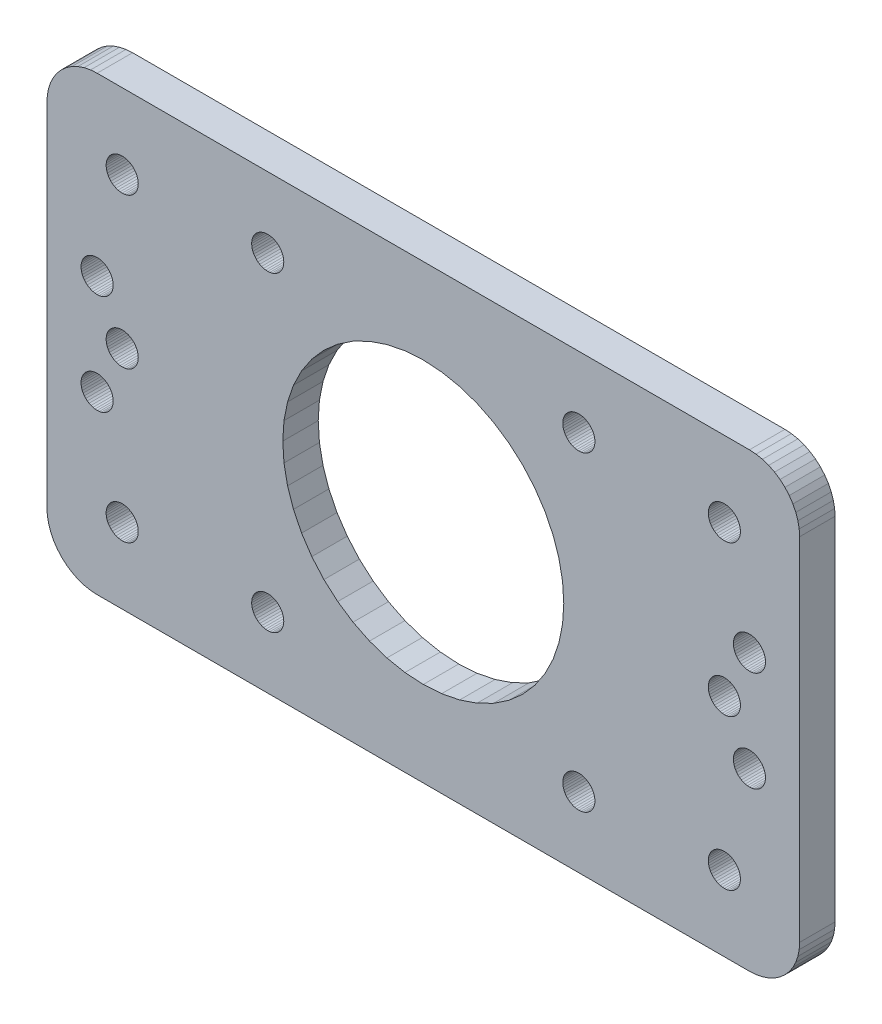
SolidWorks part; units mm, degrees
ref_plane "Front Plane" through (0, 0, 0) normal (0, 0, 1) x (1, 0, 0)
ref_plane "Top Plane" through (0, 0, 0) normal (0, 1, 0) x (1, 0, 0)
ref_plane "Right Plane" through (0, 0, 0) normal (1, 0, 0) x (0, 0, -1)
ref_plane "Plane4" through (0, 0, 3.532) normal (0, 0, 1) x (1, 0, 0)
sketch "Sketch1" plane through (0, 0, 3.532) normal (0, 0, 1) x (1, 0, 0)
  line L0 (5.9545, 22.0859) -> (5.9137, 22.2912)
  line L1 (5.9137, 22.2912) -> (5.9, 22.5)
  line L2 (5.9, 22.5) -> (5.9137, 22.7088)
  line L3 (5.9137, 22.7088) -> (5.9545, 22.9141)
  line L4 (5.9545, 22.9141) -> (6.0218, 23.1123)
  line L5 (6.0218, 23.1123) -> (6.1144, 23.3)
  line L6 (6.1144, 23.3) -> (6.2306, 23.474)
  line L7 (6.2306, 23.474) -> (6.3686, 23.6314)
  line L8 (6.3686, 23.6314) -> (6.526, 23.7694)
  line L9 (6.526, 23.7694) -> (6.7, 23.8856)
  line L10 (6.7, 23.8856) -> (6.8877, 23.9782)
  line L11 (6.8877, 23.9782) -> (7.0859, 24.0455)
  line L12 (7.0859, 24.0455) -> (7.2912, 24.0863)
  line L13 (7.2912, 24.0863) -> (7.5, 24.1)
  line L14 (7.5, 24.1) -> (7.7088, 24.0863)
  line L15 (7.7088, 24.0863) -> (7.9141, 24.0455)
  line L16 (7.9141, 24.0455) -> (8.1123, 23.9782)
  line L17 (8.1123, 23.9782) -> (8.3, 23.8856)
  line L18 (8.3, 23.8856) -> (8.474, 23.7694)
  line L19 (8.474, 23.7694) -> (8.6314, 23.6314)
  line L20 (8.6314, 23.6314) -> (8.7694, 23.474)
  line L21 (8.7694, 23.474) -> (8.8856, 23.3)
  line L22 (8.8856, 23.3) -> (8.9782, 23.1123)
  line L23 (8.9782, 23.1123) -> (9.0455, 22.9141)
  line L24 (9.0455, 22.9141) -> (9.0863, 22.7088)
  line L25 (9.0863, 22.7088) -> (9.1, 22.5)
  line L26 (9.1, 22.5) -> (9.0863, 22.2912)
  line L27 (9.0863, 22.2912) -> (9.0455, 22.0859)
  line L28 (9.0455, 22.0859) -> (8.9782, 21.8877)
  line L29 (8.9782, 21.8877) -> (8.8856, 21.7)
  line L30 (8.8856, 21.7) -> (8.7694, 21.526)
  line L31 (8.7694, 21.526) -> (8.6314, 21.3686)
  line L32 (8.6314, 21.3686) -> (8.474, 21.2306)
  line L33 (8.474, 21.2306) -> (8.3, 21.1144)
  line L34 (8.3, 21.1144) -> (8.1123, 21.0218)
  line L35 (8.1123, 21.0218) -> (7.9141, 20.9545)
  line L36 (7.9141, 20.9545) -> (7.7088, 20.9137)
  line L37 (7.7088, 20.9137) -> (7.5, 20.9)
  line L38 (7.5, 20.9) -> (7.2912, 20.9137)
  line L39 (7.2912, 20.9137) -> (7.0859, 20.9545)
  line L40 (7.0859, 20.9545) -> (6.8877, 21.0218)
  line L41 (6.8877, 21.0218) -> (6.7, 21.1144)
  line L42 (6.7, 21.1144) -> (6.526, 21.2306)
  line L43 (6.526, 21.2306) -> (6.3686, 21.3686)
  line L44 (6.3686, 21.3686) -> (6.2306, 21.526)
  line L45 (6.2306, 21.526) -> (6.1144, 21.7)
  line L46 (6.1144, 21.7) -> (6.0218, 21.8877)
  line L47 (6.0218, 21.8877) -> (5.9545, 22.0859)
  line L48 (5.6123, 18.9782) -> (5.8, 18.8856)
  line L49 (5.8, 18.8856) -> (5.974, 18.7694)
  line L50 (5.974, 18.7694) -> (6.1314, 18.6314)
  line L51 (6.1314, 18.6314) -> (6.2694, 18.474)
  line L52 (6.2694, 18.474) -> (6.3856, 18.3)
  line L53 (6.3856, 18.3) -> (6.4782, 18.1123)
  line L54 (6.4782, 18.1123) -> (6.5455, 17.9141)
  line L55 (6.5455, 17.9141) -> (6.5863, 17.7088)
  line L56 (6.5863, 17.7088) -> (6.6, 17.5)
  line L57 (6.6, 17.5) -> (6.5863, 17.2912)
  line L58 (6.5863, 17.2912) -> (6.5455, 17.0859)
  line L59 (6.5455, 17.0859) -> (6.4782, 16.8877)
  line L60 (6.4782, 16.8877) -> (6.3856, 16.7)
  line L61 (6.3856, 16.7) -> (6.2694, 16.526)
  line L62 (6.2694, 16.526) -> (6.1314, 16.3686)
  line L63 (6.1314, 16.3686) -> (5.974, 16.2306)
  line L64 (5.974, 16.2306) -> (5.8, 16.1144)
  line L65 (5.8, 16.1144) -> (5.6123, 16.0218)
  line L66 (5.6123, 16.0218) -> (5.4141, 15.9545)
  line L67 (5.4141, 15.9545) -> (5.2088, 15.9137)
  line L68 (5.2088, 15.9137) -> (5, 15.9)
  line L69 (5, 15.9) -> (4.7912, 15.9137)
  line L70 (4.7912, 15.9137) -> (4.5859, 15.9545)
  line L71 (4.5859, 15.9545) -> (4.3877, 16.0218)
  line L72 (4.3877, 16.0218) -> (4.2, 16.1144)
  line L73 (4.2, 16.1144) -> (4.026, 16.2306)
  line L74 (4.026, 16.2306) -> (3.8686, 16.3686)
  line L75 (3.8686, 16.3686) -> (3.7306, 16.526)
  line L76 (3.7306, 16.526) -> (3.6144, 16.7)
  line L77 (3.6144, 16.7) -> (3.5218, 16.8877)
  line L78 (3.5218, 16.8877) -> (3.4545, 17.0859)
  line L79 (3.4545, 17.0859) -> (3.4137, 17.2912)
  line L80 (3.4137, 17.2912) -> (3.4, 17.5)
  line L81 (3.4, 17.5) -> (3.4137, 17.7088)
  line L82 (3.4137, 17.7088) -> (3.4545, 17.9141)
  line L83 (3.4545, 17.9141) -> (3.5218, 18.1123)
  line L84 (3.5218, 18.1123) -> (3.6144, 18.3)
  line L85 (3.6144, 18.3) -> (3.7306, 18.474)
  line L86 (3.7306, 18.474) -> (3.8686, 18.6314)
  line L87 (3.8686, 18.6314) -> (4.026, 18.7694)
  line L88 (4.026, 18.7694) -> (4.2, 18.8856)
  line L89 (4.2, 18.8856) -> (4.3877, 18.9782)
  line L90 (4.3877, 18.9782) -> (4.5859, 19.0455)
  line L91 (4.5859, 19.0455) -> (4.7912, 19.0863)
  line L92 (4.7912, 19.0863) -> (5, 19.1)
  line L93 (5, 19.1) -> (5.2088, 19.0863)
  line L94 (5.2088, 19.0863) -> (5.4141, 19.0455)
  line L95 (5.4141, 19.0455) -> (5.6123, 18.9782)
  line L96 (69.3877, 18.9782) -> (69.5859, 19.0455)
  line L97 (69.5859, 19.0455) -> (69.7912, 19.0863)
  line L98 (69.7912, 19.0863) -> (70, 19.1)
  line L99 (70, 19.1) -> (70.2088, 19.0863)
  line L100 (70.2088, 19.0863) -> (70.4141, 19.0455)
  line L101 (70.4141, 19.0455) -> (70.6123, 18.9782)
  line L102 (70.6123, 18.9782) -> (70.8, 18.8856)
  line L103 (70.8, 18.8856) -> (70.974, 18.7694)
  line L104 (70.974, 18.7694) -> (71.1314, 18.6314)
  line L105 (71.1314, 18.6314) -> (71.2694, 18.474)
  line L106 (71.2694, 18.474) -> (71.3856, 18.3)
  line L107 (71.3856, 18.3) -> (71.4782, 18.1123)
  line L108 (71.4782, 18.1123) -> (71.5455, 17.9141)
  line L109 (71.5455, 17.9141) -> (71.5863, 17.7088)
  line L110 (71.5863, 17.7088) -> (71.6, 17.5)
  line L111 (71.6, 17.5) -> (71.5863, 17.2912)
  line L112 (71.5863, 17.2912) -> (71.5455, 17.0859)
  line L113 (71.5455, 17.0859) -> (71.4782, 16.8877)
  line L114 (71.4782, 16.8877) -> (71.3856, 16.7)
  line L115 (71.3856, 16.7) -> (71.2694, 16.526)
  line L116 (71.2694, 16.526) -> (71.1314, 16.3686)
  line L117 (71.1314, 16.3686) -> (70.974, 16.2306)
  line L118 (70.974, 16.2306) -> (70.8, 16.1144)
  line L119 (70.8, 16.1144) -> (70.6123, 16.0218)
  line L120 (70.6123, 16.0218) -> (70.4141, 15.9545)
  line L121 (70.4141, 15.9545) -> (70.2088, 15.9137)
  line L122 (70.2088, 15.9137) -> (70, 15.9)
  line L123 (70, 15.9) -> (69.7912, 15.9137)
  line L124 (69.7912, 15.9137) -> (69.5859, 15.9545)
  line L125 (69.5859, 15.9545) -> (69.3877, 16.0218)
  line L126 (69.3877, 16.0218) -> (69.2, 16.1144)
  line L127 (69.2, 16.1144) -> (69.026, 16.2306)
  line L128 (69.026, 16.2306) -> (68.8686, 16.3686)
  line L129 (68.8686, 16.3686) -> (68.7306, 16.526)
  line L130 (68.7306, 16.526) -> (68.6144, 16.7)
  line L131 (68.6144, 16.7) -> (68.5218, 16.8877)
  line L132 (68.5218, 16.8877) -> (68.4545, 17.0859)
  line L133 (68.4545, 17.0859) -> (68.4137, 17.2912)
  line L134 (68.4137, 17.2912) -> (68.4, 17.5)
  line L135 (68.4, 17.5) -> (68.4137, 17.7088)
  line L136 (68.4137, 17.7088) -> (68.4545, 17.9141)
  line L137 (68.4545, 17.9141) -> (68.5218, 18.1123)
  line L138 (68.5218, 18.1123) -> (68.6144, 18.3)
  line L139 (68.6144, 18.3) -> (68.7306, 18.474)
  line L140 (68.7306, 18.474) -> (68.8686, 18.6314)
  line L141 (68.8686, 18.6314) -> (69.026, 18.7694)
  line L142 (69.026, 18.7694) -> (69.2, 18.8856)
  line L143 (69.2, 18.8856) -> (69.3877, 18.9782)
  line L144 (69.0863, 22.7088) -> (69.1, 22.5)
  line L145 (69.1, 22.5) -> (69.0863, 22.2912)
  line L146 (69.0863, 22.2912) -> (69.0455, 22.0859)
  line L147 (69.0455, 22.0859) -> (68.9782, 21.8877)
  line L148 (68.9782, 21.8877) -> (68.8856, 21.7)
  line L149 (68.8856, 21.7) -> (68.7694, 21.526)
  line L150 (68.7694, 21.526) -> (68.6314, 21.3686)
  line L151 (68.6314, 21.3686) -> (68.474, 21.2306)
  line L152 (68.474, 21.2306) -> (68.3, 21.1144)
  line L153 (68.3, 21.1144) -> (68.1123, 21.0218)
  line L154 (68.1123, 21.0218) -> (67.9141, 20.9545)
  line L155 (67.9141, 20.9545) -> (67.7088, 20.9137)
  line L156 (67.7088, 20.9137) -> (67.5, 20.9)
  line L157 (67.5, 20.9) -> (67.2912, 20.9137)
  line L158 (67.2912, 20.9137) -> (67.0859, 20.9545)
  line L159 (67.0859, 20.9545) -> (66.8877, 21.0218)
  line L160 (66.8877, 21.0218) -> (66.7, 21.1144)
  line L161 (66.7, 21.1144) -> (66.526, 21.2306)
  line L162 (66.526, 21.2306) -> (66.3686, 21.3686)
  line L163 (66.3686, 21.3686) -> (66.2306, 21.526)
  line L164 (66.2306, 21.526) -> (66.1144, 21.7)
  line L165 (66.1144, 21.7) -> (66.0218, 21.8877)
  line L166 (66.0218, 21.8877) -> (65.9545, 22.0859)
  line L167 (65.9545, 22.0859) -> (65.9137, 22.2912)
  line L168 (65.9137, 22.2912) -> (65.9, 22.5)
  line L169 (65.9, 22.5) -> (65.9137, 22.7088)
  line L170 (65.9137, 22.7088) -> (65.9545, 22.9141)
  line L171 (65.9545, 22.9141) -> (66.0218, 23.1123)
  line L172 (66.0218, 23.1123) -> (66.1144, 23.3)
  line L173 (66.1144, 23.3) -> (66.2306, 23.474)
  line L174 (66.2306, 23.474) -> (66.3686, 23.6314)
  line L175 (66.3686, 23.6314) -> (66.526, 23.7694)
  line L176 (66.526, 23.7694) -> (66.7, 23.8856)
  line L177 (66.7, 23.8856) -> (66.8877, 23.9782)
  line L178 (66.8877, 23.9782) -> (67.0859, 24.0455)
  line L179 (67.0859, 24.0455) -> (67.2912, 24.0863)
  line L180 (67.2912, 24.0863) -> (67.5, 24.1)
  line L181 (67.5, 24.1) -> (67.7088, 24.0863)
  line L182 (67.7088, 24.0863) -> (67.9141, 24.0455)
  line L183 (67.9141, 24.0455) -> (68.1123, 23.9782)
  line L184 (68.1123, 23.9782) -> (68.3, 23.8856)
  line L185 (68.3, 23.8856) -> (68.474, 23.7694)
  line L186 (68.474, 23.7694) -> (68.6314, 23.6314)
  line L187 (68.6314, 23.6314) -> (68.7694, 23.474)
  line L188 (68.7694, 23.474) -> (68.8856, 23.3)
  line L189 (68.8856, 23.3) -> (68.9782, 23.1123)
  line L190 (68.9782, 23.1123) -> (69.0455, 22.9141)
  line L191 (69.0455, 22.9141) -> (69.0863, 22.7088)
  line L192 (6.3686, 8.6314) -> (6.526, 8.7694)
  line L193 (6.526, 8.7694) -> (6.7, 8.8856)
  line L194 (6.7, 8.8856) -> (6.8877, 8.9782)
  line L195 (6.8877, 8.9782) -> (7.0859, 9.0455)
  line L196 (7.0859, 9.0455) -> (7.2912, 9.0863)
  line L197 (7.2912, 9.0863) -> (7.5, 9.1)
  line L198 (7.5, 9.1) -> (7.7088, 9.0863)
  line L199 (7.7088, 9.0863) -> (7.9141, 9.0455)
  line L200 (7.9141, 9.0455) -> (8.1123, 8.9782)
  line L201 (8.1123, 8.9782) -> (8.3, 8.8856)
  line L202 (8.3, 8.8856) -> (8.474, 8.7694)
  line L203 (8.474, 8.7694) -> (8.6314, 8.6314)
  line L204 (8.6314, 8.6314) -> (8.7694, 8.474)
  line L205 (8.7694, 8.474) -> (8.8856, 8.3)
  line L206 (8.8856, 8.3) -> (8.9782, 8.1123)
  line L207 (8.9782, 8.1123) -> (9.0455, 7.9141)
  line L208 (9.0455, 7.9141) -> (9.0863, 7.7088)
  line L209 (9.0863, 7.7088) -> (9.1, 7.5)
  line L210 (9.1, 7.5) -> (9.0863, 7.2912)
  line L211 (9.0863, 7.2912) -> (9.0455, 7.0859)
  line L212 (9.0455, 7.0859) -> (8.9782, 6.8877)
  line L213 (8.9782, 6.8877) -> (8.8856, 6.7)
  line L214 (8.8856, 6.7) -> (8.7694, 6.526)
  line L215 (8.7694, 6.526) -> (8.6314, 6.3686)
  line L216 (8.6314, 6.3686) -> (8.474, 6.2306)
  line L217 (8.474, 6.2306) -> (8.3, 6.1144)
  line L218 (8.3, 6.1144) -> (8.1123, 6.0218)
  line L219 (8.1123, 6.0218) -> (7.9141, 5.9545)
  line L220 (7.9141, 5.9545) -> (7.7088, 5.9137)
  line L221 (7.7088, 5.9137) -> (7.5, 5.9)
  line L222 (7.5, 5.9) -> (7.2912, 5.9137)
  line L223 (7.2912, 5.9137) -> (7.0859, 5.9545)
  line L224 (7.0859, 5.9545) -> (6.8877, 6.0218)
  line L225 (6.8877, 6.0218) -> (6.7, 6.1144)
  line L226 (6.7, 6.1144) -> (6.526, 6.2306)
  line L227 (6.526, 6.2306) -> (6.3686, 6.3686)
  line L228 (6.3686, 6.3686) -> (6.2306, 6.526)
  line L229 (6.2306, 6.526) -> (6.1144, 6.7)
  line L230 (6.1144, 6.7) -> (6.0218, 6.8877)
  line L231 (6.0218, 6.8877) -> (5.9545, 7.0859)
  line L232 (5.9545, 7.0859) -> (5.9137, 7.2912)
  line L233 (5.9137, 7.2912) -> (5.9, 7.5)
  line L234 (5.9, 7.5) -> (5.9137, 7.7088)
  line L235 (5.9137, 7.7088) -> (5.9545, 7.9141)
  line L236 (5.9545, 7.9141) -> (6.0218, 8.1123)
  line L237 (6.0218, 8.1123) -> (6.1144, 8.3)
  line L238 (6.1144, 8.3) -> (6.2306, 8.474)
  line L239 (6.2306, 8.474) -> (6.3686, 8.6314)
  line L240 (68.3, 8.8856) -> (68.474, 8.7694)
  line L241 (68.474, 8.7694) -> (68.6314, 8.6314)
  line L242 (68.6314, 8.6314) -> (68.7694, 8.474)
  line L243 (68.7694, 8.474) -> (68.8856, 8.3)
  line L244 (68.8856, 8.3) -> (68.9782, 8.1123)
  line L245 (68.9782, 8.1123) -> (69.0455, 7.9141)
  line L246 (69.0455, 7.9141) -> (69.0863, 7.7088)
  line L247 (69.0863, 7.7088) -> (69.1, 7.5)
  line L248 (69.1, 7.5) -> (69.0863, 7.2912)
  line L249 (69.0863, 7.2912) -> (69.0455, 7.0859)
  line L250 (69.0455, 7.0859) -> (68.9782, 6.8877)
  line L251 (68.9782, 6.8877) -> (68.8856, 6.7)
  line L252 (68.8856, 6.7) -> (68.7694, 6.526)
  line L253 (68.7694, 6.526) -> (68.6314, 6.3686)
  line L254 (68.6314, 6.3686) -> (68.474, 6.2306)
  line L255 (68.474, 6.2306) -> (68.3, 6.1144)
  line L256 (68.3, 6.1144) -> (68.1123, 6.0218)
  line L257 (68.1123, 6.0218) -> (67.9141, 5.9545)
  line L258 (67.9141, 5.9545) -> (67.7088, 5.9137)
  line L259 (67.7088, 5.9137) -> (67.5, 5.9)
  line L260 (67.5, 5.9) -> (67.2912, 5.9137)
  line L261 (67.2912, 5.9137) -> (67.0859, 5.9545)
  line L262 (67.0859, 5.9545) -> (66.8877, 6.0218)
  line L263 (66.8877, 6.0218) -> (66.7, 6.1144)
  line L264 (66.7, 6.1144) -> (66.526, 6.2306)
  line L265 (66.526, 6.2306) -> (66.3686, 6.3686)
  line L266 (66.3686, 6.3686) -> (66.2306, 6.526)
  line L267 (66.2306, 6.526) -> (66.1144, 6.7)
  line L268 (66.1144, 6.7) -> (66.0218, 6.8877)
  line L269 (66.0218, 6.8877) -> (65.9545, 7.0859)
  line L270 (65.9545, 7.0859) -> (65.9137, 7.2912)
  line L271 (65.9137, 7.2912) -> (65.9, 7.5)
  line L272 (65.9, 7.5) -> (65.9137, 7.7088)
  line L273 (65.9137, 7.7088) -> (65.9545, 7.9141)
  line L274 (65.9545, 7.9141) -> (66.0218, 8.1123)
  line L275 (66.0218, 8.1123) -> (66.1144, 8.3)
  line L276 (66.1144, 8.3) -> (66.2306, 8.474)
  line L277 (66.2306, 8.474) -> (66.3686, 8.6314)
  line L278 (66.3686, 8.6314) -> (66.526, 8.7694)
  line L279 (66.526, 8.7694) -> (66.7, 8.8856)
  line L280 (66.7, 8.8856) -> (66.8877, 8.9782)
  line L281 (66.8877, 8.9782) -> (67.0859, 9.0455)
  line L282 (67.0859, 9.0455) -> (67.2912, 9.0863)
  line L283 (67.2912, 9.0863) -> (67.5, 9.1)
  line L284 (67.5, 9.1) -> (67.7088, 9.0863)
  line L285 (67.7088, 9.0863) -> (67.9141, 9.0455)
  line L286 (67.9141, 9.0455) -> (68.1123, 8.9782)
  line L287 (68.1123, 8.9782) -> (68.3, 8.8856)
  line L288 (6.5863, 27.7088) -> (6.6, 27.5)
  line L289 (6.6, 27.5) -> (6.5863, 27.2912)
  line L290 (6.5863, 27.2912) -> (6.5455, 27.0859)
  line L291 (6.5455, 27.0859) -> (6.4782, 26.8877)
  line L292 (6.4782, 26.8877) -> (6.3856, 26.7)
  line L293 (6.3856, 26.7) -> (6.2694, 26.526)
  line L294 (6.2694, 26.526) -> (6.1314, 26.3686)
  line L295 (6.1314, 26.3686) -> (5.974, 26.2306)
  line L296 (5.974, 26.2306) -> (5.8, 26.1144)
  line L297 (5.8, 26.1144) -> (5.6123, 26.0218)
  line L298 (5.6123, 26.0218) -> (5.4141, 25.9545)
  line L299 (5.4141, 25.9545) -> (5.2088, 25.9137)
  line L300 (5.2088, 25.9137) -> (5, 25.9)
  line L301 (5, 25.9) -> (4.7912, 25.9137)
  line L302 (4.7912, 25.9137) -> (4.5859, 25.9545)
  line L303 (4.5859, 25.9545) -> (4.3877, 26.0218)
  line L304 (4.3877, 26.0218) -> (4.2, 26.1144)
  line L305 (4.2, 26.1144) -> (4.026, 26.2306)
  line L306 (4.026, 26.2306) -> (3.8686, 26.3686)
  line L307 (3.8686, 26.3686) -> (3.7306, 26.526)
  line L308 (3.7306, 26.526) -> (3.6144, 26.7)
  line L309 (3.6144, 26.7) -> (3.5218, 26.8877)
  line L310 (3.5218, 26.8877) -> (3.4545, 27.0859)
  line L311 (3.4545, 27.0859) -> (3.4137, 27.2912)
  line L312 (3.4137, 27.2912) -> (3.4, 27.5)
  line L313 (3.4, 27.5) -> (3.4137, 27.7088)
  line L314 (3.4137, 27.7088) -> (3.4545, 27.9141)
  line L315 (3.4545, 27.9141) -> (3.5218, 28.1123)
  line L316 (3.5218, 28.1123) -> (3.6144, 28.3)
  line L317 (3.6144, 28.3) -> (3.7306, 28.474)
  line L318 (3.7306, 28.474) -> (3.8686, 28.6314)
  line L319 (3.8686, 28.6314) -> (4.026, 28.7694)
  line L320 (4.026, 28.7694) -> (4.2, 28.8856)
  line L321 (4.2, 28.8856) -> (4.3877, 28.9782)
  line L322 (4.3877, 28.9782) -> (4.5859, 29.0455)
  line L323 (4.5859, 29.0455) -> (4.7912, 29.0863)
  line L324 (4.7912, 29.0863) -> (5, 29.1)
  line L325 (5, 29.1) -> (5.2088, 29.0863)
  line L326 (5.2088, 29.0863) -> (5.4141, 29.0455)
  line L327 (5.4141, 29.0455) -> (5.6123, 28.9782)
  line L328 (5.6123, 28.9782) -> (5.8, 28.8856)
  line L329 (5.8, 28.8856) -> (5.974, 28.7694)
  line L330 (5.974, 28.7694) -> (6.1314, 28.6314)
  line L331 (6.1314, 28.6314) -> (6.2694, 28.474)
  line L332 (6.2694, 28.474) -> (6.3856, 28.3)
  line L333 (6.3856, 28.3) -> (6.4782, 28.1123)
  line L334 (6.4782, 28.1123) -> (6.5455, 27.9141)
  line L335 (6.5455, 27.9141) -> (6.5863, 27.7088)
  line L336 (68.3, 36.1144) -> (68.1123, 36.0218)
  line L337 (68.1123, 36.0218) -> (67.9141, 35.9545)
  line L338 (67.9141, 35.9545) -> (67.7088, 35.9137)
  line L339 (67.7088, 35.9137) -> (67.5, 35.9)
  line L340 (67.5, 35.9) -> (67.2912, 35.9137)
  line L341 (67.2912, 35.9137) -> (67.0859, 35.9545)
  line L342 (67.0859, 35.9545) -> (66.8877, 36.0218)
  line L343 (66.8877, 36.0218) -> (66.7, 36.1144)
  line L344 (66.7, 36.1144) -> (66.526, 36.2306)
  line L345 (66.526, 36.2306) -> (66.3686, 36.3686)
  line L346 (66.3686, 36.3686) -> (66.2306, 36.526)
  line L347 (66.2306, 36.526) -> (66.1144, 36.7)
  line L348 (66.1144, 36.7) -> (66.0218, 36.8877)
  line L349 (66.0218, 36.8877) -> (65.9545, 37.0859)
  line L350 (65.9545, 37.0859) -> (65.9137, 37.2912)
  line L351 (65.9137, 37.2912) -> (65.9, 37.5)
  line L352 (65.9, 37.5) -> (65.9137, 37.7088)
  line L353 (65.9137, 37.7088) -> (65.9545, 37.9141)
  line L354 (65.9545, 37.9141) -> (66.0218, 38.1123)
  line L355 (66.0218, 38.1123) -> (66.1144, 38.3)
  line L356 (66.1144, 38.3) -> (66.2306, 38.474)
  line L357 (66.2306, 38.474) -> (66.3686, 38.6314)
  line L358 (66.3686, 38.6314) -> (66.526, 38.7694)
  line L359 (66.526, 38.7694) -> (66.7, 38.8856)
  line L360 (66.7, 38.8856) -> (66.8877, 38.9782)
  line L361 (66.8877, 38.9782) -> (67.0859, 39.0455)
  line L362 (67.0859, 39.0455) -> (67.2912, 39.0863)
  line L363 (67.2912, 39.0863) -> (67.5, 39.1)
  line L364 (67.5, 39.1) -> (67.7088, 39.0863)
  line L365 (67.7088, 39.0863) -> (67.9141, 39.0455)
  line L366 (67.9141, 39.0455) -> (68.1123, 38.9782)
  line L367 (68.1123, 38.9782) -> (68.3, 38.8856)
  line L368 (68.3, 38.8856) -> (68.474, 38.7694)
  line L369 (68.474, 38.7694) -> (68.6314, 38.6314)
  line L370 (68.6314, 38.6314) -> (68.7694, 38.474)
  line L371 (68.7694, 38.474) -> (68.8856, 38.3)
  line L372 (68.8856, 38.3) -> (68.9782, 38.1123)
  line L373 (68.9782, 38.1123) -> (69.0455, 37.9141)
  line L374 (69.0455, 37.9141) -> (69.0863, 37.7088)
  line L375 (69.0863, 37.7088) -> (69.1, 37.5)
  line L376 (69.1, 37.5) -> (69.0863, 37.2912)
  line L377 (69.0863, 37.2912) -> (69.0455, 37.0859)
  line L378 (69.0455, 37.0859) -> (68.9782, 36.8877)
  line L379 (68.9782, 36.8877) -> (68.8856, 36.7)
  line L380 (68.8856, 36.7) -> (68.7694, 36.526)
  line L381 (68.7694, 36.526) -> (68.6314, 36.3686)
  line L382 (68.6314, 36.3686) -> (68.474, 36.2306)
  line L383 (68.474, 36.2306) -> (68.3, 36.1144)
  line L384 (6.8877, 36.0218) -> (6.7, 36.1144)
  line L385 (6.7, 36.1144) -> (6.526, 36.2306)
  line L386 (6.526, 36.2306) -> (6.3686, 36.3686)
  line L387 (6.3686, 36.3686) -> (6.2306, 36.526)
  line L388 (6.2306, 36.526) -> (6.1144, 36.7)
  line L389 (6.1144, 36.7) -> (6.0218, 36.8877)
  line L390 (6.0218, 36.8877) -> (5.9545, 37.0859)
  line L391 (5.9545, 37.0859) -> (5.9137, 37.2912)
  line L392 (5.9137, 37.2912) -> (5.9, 37.5)
  line L393 (5.9, 37.5) -> (5.9137, 37.7088)
  line L394 (5.9137, 37.7088) -> (5.9545, 37.9141)
  line L395 (5.9545, 37.9141) -> (6.0218, 38.1123)
  line L396 (6.0218, 38.1123) -> (6.1144, 38.3)
  line L397 (6.1144, 38.3) -> (6.2306, 38.474)
  line L398 (6.2306, 38.474) -> (6.3686, 38.6314)
  line L399 (6.3686, 38.6314) -> (6.526, 38.7694)
  line L400 (6.526, 38.7694) -> (6.7, 38.8856)
  line L401 (6.7, 38.8856) -> (6.8877, 38.9782)
  line L402 (6.8877, 38.9782) -> (7.0859, 39.0455)
  line L403 (7.0859, 39.0455) -> (7.2912, 39.0863)
  line L404 (7.2912, 39.0863) -> (7.5, 39.1)
  line L405 (7.5, 39.1) -> (7.7088, 39.0863)
  line L406 (7.7088, 39.0863) -> (7.9141, 39.0455)
  line L407 (7.9141, 39.0455) -> (8.1123, 38.9782)
  line L408 (8.1123, 38.9782) -> (8.3, 38.8856)
  line L409 (8.3, 38.8856) -> (8.474, 38.7694)
  line L410 (8.474, 38.7694) -> (8.6314, 38.6314)
  line L411 (8.6314, 38.6314) -> (8.7694, 38.474)
  line L412 (8.7694, 38.474) -> (8.8856, 38.3)
  line L413 (8.8856, 38.3) -> (8.9782, 38.1123)
  line L414 (8.9782, 38.1123) -> (9.0455, 37.9141)
  line L415 (9.0455, 37.9141) -> (9.0863, 37.7088)
  line L416 (9.0863, 37.7088) -> (9.1, 37.5)
  line L417 (9.1, 37.5) -> (9.0863, 37.2912)
  line L418 (9.0863, 37.2912) -> (9.0455, 37.0859)
  line L419 (9.0455, 37.0859) -> (8.9782, 36.8877)
  line L420 (8.9782, 36.8877) -> (8.8856, 36.7)
  line L421 (8.8856, 36.7) -> (8.7694, 36.526)
  line L422 (8.7694, 36.526) -> (8.6314, 36.3686)
  line L423 (8.6314, 36.3686) -> (8.474, 36.2306)
  line L424 (8.474, 36.2306) -> (8.3, 36.1144)
  line L425 (8.3, 36.1144) -> (8.1123, 36.0218)
  line L426 (8.1123, 36.0218) -> (7.9141, 35.9545)
  line L427 (7.9141, 35.9545) -> (7.7088, 35.9137)
  line L428 (7.7088, 35.9137) -> (7.5, 35.9)
  line L429 (7.5, 35.9) -> (7.2912, 35.9137)
  line L430 (7.2912, 35.9137) -> (7.0859, 35.9545)
  line L431 (7.0859, 35.9545) -> (6.8877, 36.0218)
  line L432 (70, 0) -> (70.6526, 0.0428)
  line L433 (70.6526, 0.0428) -> (71.2941, 0.1704)
  line L434 (71.2941, 0.1704) -> (71.9134, 0.3806)
  line L435 (71.9134, 0.3806) -> (72.5, 0.6699)
  line L436 (72.5, 0.6699) -> (73.0438, 1.0332)
  line L437 (73.0438, 1.0332) -> (73.5355, 1.4645)
  line L438 (73.5355, 1.4645) -> (73.9668, 1.9562)
  line L439 (73.9668, 1.9562) -> (74.3301, 2.5)
  line L440 (74.3301, 2.5) -> (74.6194, 3.0866)
  line L441 (74.6194, 3.0866) -> (74.8296, 3.7059)
  line L442 (74.8296, 3.7059) -> (74.9572, 4.3474)
  line L443 (74.9572, 4.3474) -> (75, 5)
  line L444 (75, 5) -> (75, 40)
  line L445 (75, 40) -> (74.9572, 40.6526)
  line L446 (74.9572, 40.6526) -> (74.8296, 41.2941)
  line L447 (74.8296, 41.2941) -> (74.6194, 41.9134)
  line L448 (74.6194, 41.9134) -> (74.3301, 42.5)
  line L449 (74.3301, 42.5) -> (73.9668, 43.0438)
  line L450 (73.9668, 43.0438) -> (73.5355, 43.5355)
  line L451 (73.5355, 43.5355) -> (73.0438, 43.9668)
  line L452 (73.0438, 43.9668) -> (72.5, 44.3301)
  line L453 (72.5, 44.3301) -> (71.9134, 44.6194)
  line L454 (71.9134, 44.6194) -> (71.2941, 44.8296)
  line L455 (71.2941, 44.8296) -> (70.6526, 44.9572)
  line L456 (70.6526, 44.9572) -> (70, 45)
  line L457 (70, 45) -> (5, 45)
  line L458 (5, 45) -> (4.3474, 44.9572)
  line L459 (4.3474, 44.9572) -> (3.7059, 44.8296)
  line L460 (3.7059, 44.8296) -> (3.0866, 44.6194)
  line L461 (3.0866, 44.6194) -> (2.5, 44.3301)
  line L462 (2.5, 44.3301) -> (1.9562, 43.9668)
  line L463 (1.9562, 43.9668) -> (1.4645, 43.5355)
  line L464 (1.4645, 43.5355) -> (1.0332, 43.0438)
  line L465 (1.0332, 43.0438) -> (0.6699, 42.5)
  line L466 (0.6699, 42.5) -> (0.3806, 41.9134)
  line L467 (0.3806, 41.9134) -> (0.1704, 41.2941)
  line L468 (0.1704, 41.2941) -> (0.0428, 40.6526)
  line L469 (0.0428, 40.6526) -> (0, 40)
  line L470 (0, 40) -> (0, 5)
  line L471 (0, 5) -> (0.0428, 4.3474)
  line L472 (0.0428, 4.3474) -> (0.1704, 3.7059)
  line L473 (0.1704, 3.7059) -> (0.3806, 3.0866)
  line L474 (0.3806, 3.0866) -> (0.6699, 2.5)
  line L475 (0.6699, 2.5) -> (1.0332, 1.9562)
  line L476 (1.0332, 1.9562) -> (1.4645, 1.4645)
  line L477 (1.4645, 1.4645) -> (1.9562, 1.0332)
  line L478 (1.9562, 1.0332) -> (2.5, 0.6699)
  line L479 (2.5, 0.6699) -> (3.0866, 0.3806)
  line L480 (3.0866, 0.3806) -> (3.7059, 0.1704)
  line L481 (3.7059, 0.1704) -> (4.3474, 0.0428)
  line L482 (4.3474, 0.0428) -> (5, 0)
  line L483 (5, 0) -> (70, 0)
  line L484 (20.7306, 7.974) -> (20.8686, 8.1314)
  line L485 (20.8686, 8.1314) -> (21.026, 8.2694)
  line L486 (21.026, 8.2694) -> (21.2, 8.3856)
  line L487 (21.2, 8.3856) -> (21.3877, 8.4782)
  line L488 (21.3877, 8.4782) -> (21.5859, 8.5455)
  line L489 (21.5859, 8.5455) -> (21.7912, 8.5863)
  line L490 (21.7912, 8.5863) -> (22, 8.6)
  line L491 (22, 8.6) -> (22.2088, 8.5863)
  line L492 (22.2088, 8.5863) -> (22.4141, 8.5455)
  line L493 (22.4141, 8.5455) -> (22.6123, 8.4782)
  line L494 (22.6123, 8.4782) -> (22.8, 8.3856)
  line L495 (22.8, 8.3856) -> (22.974, 8.2694)
  line L496 (22.974, 8.2694) -> (23.1314, 8.1314)
  line L497 (23.1314, 8.1314) -> (23.2694, 7.974)
  line L498 (23.2694, 7.974) -> (23.3856, 7.8)
  line L499 (23.3856, 7.8) -> (23.4782, 7.6123)
  line L500 (23.4782, 7.6123) -> (23.5455, 7.4141)
  line L501 (23.5455, 7.4141) -> (23.5863, 7.2088)
  line L502 (23.5863, 7.2088) -> (23.6, 7)
  line L503 (23.6, 7) -> (23.5863, 6.7912)
  line L504 (23.5863, 6.7912) -> (23.5455, 6.5859)
  line L505 (23.5455, 6.5859) -> (23.4782, 6.3877)
  line L506 (23.4782, 6.3877) -> (23.3856, 6.2)
  line L507 (23.3856, 6.2) -> (23.2694, 6.026)
  line L508 (23.2694, 6.026) -> (23.1314, 5.8686)
  line L509 (23.1314, 5.8686) -> (22.974, 5.7306)
  line L510 (22.974, 5.7306) -> (22.8, 5.6144)
  line L511 (22.8, 5.6144) -> (22.6123, 5.5218)
  line L512 (22.6123, 5.5218) -> (22.4141, 5.4545)
  line L513 (22.4141, 5.4545) -> (22.2088, 5.4137)
  line L514 (22.2088, 5.4137) -> (22, 5.4)
  line L515 (22, 5.4) -> (21.7912, 5.4137)
  line L516 (21.7912, 5.4137) -> (21.5859, 5.4545)
  line L517 (21.5859, 5.4545) -> (21.3877, 5.5218)
  line L518 (21.3877, 5.5218) -> (21.2, 5.6144)
  line L519 (21.2, 5.6144) -> (21.026, 5.7306)
  line L520 (21.026, 5.7306) -> (20.8686, 5.8686)
  line L521 (20.8686, 5.8686) -> (20.7306, 6.026)
  line L522 (20.7306, 6.026) -> (20.6144, 6.2)
  line L523 (20.6144, 6.2) -> (20.5218, 6.3877)
  line L524 (20.5218, 6.3877) -> (20.4545, 6.5859)
  line L525 (20.4545, 6.5859) -> (20.4137, 6.7912)
  line L526 (20.4137, 6.7912) -> (20.4, 7)
  line L527 (20.4, 7) -> (20.4137, 7.2088)
  line L528 (20.4137, 7.2088) -> (20.4545, 7.4141)
  line L529 (20.4545, 7.4141) -> (20.5218, 7.6123)
  line L530 (20.5218, 7.6123) -> (20.6144, 7.8)
  line L531 (20.6144, 7.8) -> (20.7306, 7.974)
  line L532 (21.026, 36.7306) -> (20.8686, 36.8686)
  line L533 (20.8686, 36.8686) -> (20.7306, 37.026)
  line L534 (20.7306, 37.026) -> (20.6144, 37.2)
  line L535 (20.6144, 37.2) -> (20.5218, 37.3877)
  line L536 (20.5218, 37.3877) -> (20.4545, 37.5859)
  line L537 (20.4545, 37.5859) -> (20.4137, 37.7912)
  line L538 (20.4137, 37.7912) -> (20.4, 38)
  line L539 (20.4, 38) -> (20.4137, 38.2088)
  line L540 (20.4137, 38.2088) -> (20.4545, 38.4141)
  line L541 (20.4545, 38.4141) -> (20.5218, 38.6123)
  line L542 (20.5218, 38.6123) -> (20.6144, 38.8)
  line L543 (20.6144, 38.8) -> (20.7306, 38.974)
  line L544 (20.7306, 38.974) -> (20.8686, 39.1314)
  line L545 (20.8686, 39.1314) -> (21.026, 39.2694)
  line L546 (21.026, 39.2694) -> (21.2, 39.3856)
  line L547 (21.2, 39.3856) -> (21.3877, 39.4782)
  line L548 (21.3877, 39.4782) -> (21.5859, 39.5455)
  line L549 (21.5859, 39.5455) -> (21.7912, 39.5863)
  line L550 (21.7912, 39.5863) -> (22, 39.6)
  line L551 (22, 39.6) -> (22.2088, 39.5863)
  line L552 (22.2088, 39.5863) -> (22.4141, 39.5455)
  line L553 (22.4141, 39.5455) -> (22.6123, 39.4782)
  line L554 (22.6123, 39.4782) -> (22.8, 39.3856)
  line L555 (22.8, 39.3856) -> (22.974, 39.2694)
  line L556 (22.974, 39.2694) -> (23.1314, 39.1314)
  line L557 (23.1314, 39.1314) -> (23.2694, 38.974)
  line L558 (23.2694, 38.974) -> (23.3856, 38.8)
  line L559 (23.3856, 38.8) -> (23.4782, 38.6123)
  line L560 (23.4782, 38.6123) -> (23.5455, 38.4141)
  line L561 (23.5455, 38.4141) -> (23.5863, 38.2088)
  line L562 (23.5863, 38.2088) -> (23.6, 38)
  line L563 (23.6, 38) -> (23.5863, 37.7912)
  line L564 (23.5863, 37.7912) -> (23.5455, 37.5859)
  line L565 (23.5455, 37.5859) -> (23.4782, 37.3877)
  line L566 (23.4782, 37.3877) -> (23.3856, 37.2)
  line L567 (23.3856, 37.2) -> (23.2694, 37.026)
  line L568 (23.2694, 37.026) -> (23.1314, 36.8686)
  line L569 (23.1314, 36.8686) -> (22.974, 36.7306)
  line L570 (22.974, 36.7306) -> (22.8, 36.6144)
  line L571 (22.8, 36.6144) -> (22.6123, 36.5218)
  line L572 (22.6123, 36.5218) -> (22.4141, 36.4545)
  line L573 (22.4141, 36.4545) -> (22.2088, 36.4137)
  line L574 (22.2088, 36.4137) -> (22, 36.4)
  line L575 (22, 36.4) -> (21.7912, 36.4137)
  line L576 (21.7912, 36.4137) -> (21.5859, 36.4545)
  line L577 (21.5859, 36.4545) -> (21.3877, 36.5218)
  line L578 (21.3877, 36.5218) -> (21.2, 36.6144)
  line L579 (21.2, 36.6144) -> (21.026, 36.7306)
  line L580 (53.6123, 8.4782) -> (53.8, 8.3856)
  line L581 (53.8, 8.3856) -> (53.974, 8.2694)
  line L582 (53.974, 8.2694) -> (54.1314, 8.1314)
  line L583 (54.1314, 8.1314) -> (54.2694, 7.974)
  line L584 (54.2694, 7.974) -> (54.3856, 7.8)
  line L585 (54.3856, 7.8) -> (54.4782, 7.6123)
  line L586 (54.4782, 7.6123) -> (54.5455, 7.4141)
  line L587 (54.5455, 7.4141) -> (54.5863, 7.2088)
  line L588 (54.5863, 7.2088) -> (54.6, 7)
  line L589 (54.6, 7) -> (54.5863, 6.7912)
  line L590 (54.5863, 6.7912) -> (54.5455, 6.5859)
  line L591 (54.5455, 6.5859) -> (54.4782, 6.3877)
  line L592 (54.4782, 6.3877) -> (54.3856, 6.2)
  line L593 (54.3856, 6.2) -> (54.2694, 6.026)
  line L594 (54.2694, 6.026) -> (54.1314, 5.8686)
  line L595 (54.1314, 5.8686) -> (53.974, 5.7306)
  line L596 (53.974, 5.7306) -> (53.8, 5.6144)
  line L597 (53.8, 5.6144) -> (53.6123, 5.5218)
  line L598 (53.6123, 5.5218) -> (53.4141, 5.4545)
  line L599 (53.4141, 5.4545) -> (53.2088, 5.4137)
  line L600 (53.2088, 5.4137) -> (53, 5.4)
  line L601 (53, 5.4) -> (52.7912, 5.4137)
  line L602 (52.7912, 5.4137) -> (52.5859, 5.4545)
  line L603 (52.5859, 5.4545) -> (52.3877, 5.5218)
  line L604 (52.3877, 5.5218) -> (52.2, 5.6144)
  line L605 (52.2, 5.6144) -> (52.026, 5.7306)
  line L606 (52.026, 5.7306) -> (51.8686, 5.8686)
  line L607 (51.8686, 5.8686) -> (51.7306, 6.026)
  line L608 (51.7306, 6.026) -> (51.6144, 6.2)
  line L609 (51.6144, 6.2) -> (51.5218, 6.3877)
  line L610 (51.5218, 6.3877) -> (51.4545, 6.5859)
  line L611 (51.4545, 6.5859) -> (51.4137, 6.7912)
  line L612 (51.4137, 6.7912) -> (51.4, 7)
  line L613 (51.4, 7) -> (51.4137, 7.2088)
  line L614 (51.4137, 7.2088) -> (51.4545, 7.4141)
  line L615 (51.4545, 7.4141) -> (51.5218, 7.6123)
  line L616 (51.5218, 7.6123) -> (51.6144, 7.8)
  line L617 (51.6144, 7.8) -> (51.7306, 7.974)
  line L618 (51.7306, 7.974) -> (51.8686, 8.1314)
  line L619 (51.8686, 8.1314) -> (52.026, 8.2694)
  line L620 (52.026, 8.2694) -> (52.2, 8.3856)
  line L621 (52.2, 8.3856) -> (52.3877, 8.4782)
  line L622 (52.3877, 8.4782) -> (52.5859, 8.5455)
  line L623 (52.5859, 8.5455) -> (52.7912, 8.5863)
  line L624 (52.7912, 8.5863) -> (53, 8.6)
  line L625 (53, 8.6) -> (53.2088, 8.5863)
  line L626 (53.2088, 8.5863) -> (53.4141, 8.5455)
  line L627 (53.4141, 8.5455) -> (53.6123, 8.4782)
  line L628 (69.7912, 25.9137) -> (69.5859, 25.9545)
  line L629 (69.5859, 25.9545) -> (69.3877, 26.0218)
  line L630 (69.3877, 26.0218) -> (69.2, 26.1144)
  line L631 (69.2, 26.1144) -> (69.026, 26.2306)
  line L632 (69.026, 26.2306) -> (68.8686, 26.3686)
  line L633 (68.8686, 26.3686) -> (68.7306, 26.526)
  line L634 (68.7306, 26.526) -> (68.6144, 26.7)
  line L635 (68.6144, 26.7) -> (68.5218, 26.8877)
  line L636 (68.5218, 26.8877) -> (68.4545, 27.0859)
  line L637 (68.4545, 27.0859) -> (68.4137, 27.2912)
  line L638 (68.4137, 27.2912) -> (68.4, 27.5)
  line L639 (68.4, 27.5) -> (68.4137, 27.7088)
  line L640 (68.4137, 27.7088) -> (68.4545, 27.9141)
  line L641 (68.4545, 27.9141) -> (68.5218, 28.1123)
  line L642 (68.5218, 28.1123) -> (68.6144, 28.3)
  line L643 (68.6144, 28.3) -> (68.7306, 28.474)
  line L644 (68.7306, 28.474) -> (68.8686, 28.6314)
  line L645 (68.8686, 28.6314) -> (69.026, 28.7694)
  line L646 (69.026, 28.7694) -> (69.2, 28.8856)
  line L647 (69.2, 28.8856) -> (69.3877, 28.9782)
  line L648 (69.3877, 28.9782) -> (69.5859, 29.0455)
  line L649 (69.5859, 29.0455) -> (69.7912, 29.0863)
  line L650 (69.7912, 29.0863) -> (70, 29.1)
  line L651 (70, 29.1) -> (70.2088, 29.0863)
  line L652 (70.2088, 29.0863) -> (70.4141, 29.0455)
  line L653 (70.4141, 29.0455) -> (70.6123, 28.9782)
  line L654 (70.6123, 28.9782) -> (70.8, 28.8856)
  line L655 (70.8, 28.8856) -> (70.974, 28.7694)
  line L656 (70.974, 28.7694) -> (71.1314, 28.6314)
  line L657 (71.1314, 28.6314) -> (71.2694, 28.474)
  line L658 (71.2694, 28.474) -> (71.3856, 28.3)
  line L659 (71.3856, 28.3) -> (71.4782, 28.1123)
  line L660 (71.4782, 28.1123) -> (71.5455, 27.9141)
  line L661 (71.5455, 27.9141) -> (71.5863, 27.7088)
  line L662 (71.5863, 27.7088) -> (71.6, 27.5)
  line L663 (71.6, 27.5) -> (71.5863, 27.2912)
  line L664 (71.5863, 27.2912) -> (71.5455, 27.0859)
  line L665 (71.5455, 27.0859) -> (71.4782, 26.8877)
  line L666 (71.4782, 26.8877) -> (71.3856, 26.7)
  line L667 (71.3856, 26.7) -> (71.2694, 26.526)
  line L668 (71.2694, 26.526) -> (71.1314, 26.3686)
  line L669 (71.1314, 26.3686) -> (70.974, 26.2306)
  line L670 (70.974, 26.2306) -> (70.8, 26.1144)
  line L671 (70.8, 26.1144) -> (70.6123, 26.0218)
  line L672 (70.6123, 26.0218) -> (70.4141, 25.9545)
  line L673 (70.4141, 25.9545) -> (70.2088, 25.9137)
  line L674 (70.2088, 25.9137) -> (70, 25.9)
  line L675 (70, 25.9) -> (69.7912, 25.9137)
  line L676 (42.8576, 9.5657) -> (41.1235, 8.977)
  line L677 (41.1235, 8.977) -> (39.3274, 8.6198)
  line L678 (39.3274, 8.6198) -> (37.5, 8.5)
  line L679 (37.5, 8.5) -> (35.6726, 8.6198)
  line L680 (35.6726, 8.6198) -> (33.8765, 8.977)
  line L681 (33.8765, 8.977) -> (32.1424, 9.5657)
  line L682 (32.1424, 9.5657) -> (30.5, 10.3756)
  line L683 (30.5, 10.3756) -> (28.9773, 11.3931)
  line L684 (28.9773, 11.3931) -> (27.6005, 12.6005)
  line L685 (27.6005, 12.6005) -> (26.3931, 13.9773)
  line L686 (26.3931, 13.9773) -> (25.3756, 15.5)
  line L687 (25.3756, 15.5) -> (24.5657, 17.1424)
  line L688 (24.5657, 17.1424) -> (23.977, 18.8765)
  line L689 (23.977, 18.8765) -> (23.6198, 20.6726)
  line L690 (23.6198, 20.6726) -> (23.5, 22.5)
  line L691 (23.5, 22.5) -> (23.6198, 24.3274)
  line L692 (23.6198, 24.3274) -> (23.977, 26.1235)
  line L693 (23.977, 26.1235) -> (24.5657, 27.8576)
  line L694 (24.5657, 27.8576) -> (25.3756, 29.5)
  line L695 (25.3756, 29.5) -> (26.3931, 31.0227)
  line L696 (26.3931, 31.0227) -> (27.6005, 32.3995)
  line L697 (27.6005, 32.3995) -> (28.9773, 33.6069)
  line L698 (28.9773, 33.6069) -> (30.5, 34.6244)
  line L699 (30.5, 34.6244) -> (32.1424, 35.4343)
  line L700 (32.1424, 35.4343) -> (33.8765, 36.023)
  line L701 (33.8765, 36.023) -> (35.6726, 36.3802)
  line L702 (35.6726, 36.3802) -> (37.5, 36.5)
  line L703 (37.5, 36.5) -> (39.3274, 36.3802)
  line L704 (39.3274, 36.3802) -> (41.1235, 36.023)
  line L705 (41.1235, 36.023) -> (42.8576, 35.4343)
  line L706 (42.8576, 35.4343) -> (44.5, 34.6244)
  line L707 (44.5, 34.6244) -> (46.0227, 33.6069)
  line L708 (46.0227, 33.6069) -> (47.3995, 32.3995)
  line L709 (47.3995, 32.3995) -> (48.6069, 31.0227)
  line L710 (48.6069, 31.0227) -> (49.6244, 29.5)
  line L711 (49.6244, 29.5) -> (50.4343, 27.8576)
  line L712 (50.4343, 27.8576) -> (51.023, 26.1235)
  line L713 (51.023, 26.1235) -> (51.3802, 24.3274)
  line L714 (51.3802, 24.3274) -> (51.5, 22.5)
  line L715 (51.5, 22.5) -> (51.3802, 20.6726)
  line L716 (51.3802, 20.6726) -> (51.023, 18.8765)
  line L717 (51.023, 18.8765) -> (50.4343, 17.1424)
  line L718 (50.4343, 17.1424) -> (49.6244, 15.5)
  line L719 (49.6244, 15.5) -> (48.6069, 13.9773)
  line L720 (48.6069, 13.9773) -> (47.3995, 12.6005)
  line L721 (47.3995, 12.6005) -> (46.0227, 11.3931)
  line L722 (46.0227, 11.3931) -> (44.5, 10.3756)
  line L723 (44.5, 10.3756) -> (42.8576, 9.5657)
  line L724 (51.6144, 38.8) -> (51.7306, 38.974)
  line L725 (51.7306, 38.974) -> (51.8686, 39.1314)
  line L726 (51.8686, 39.1314) -> (52.026, 39.2694)
  line L727 (52.026, 39.2694) -> (52.2, 39.3856)
  line L728 (52.2, 39.3856) -> (52.3877, 39.4782)
  line L729 (52.3877, 39.4782) -> (52.5859, 39.5455)
  line L730 (52.5859, 39.5455) -> (52.7912, 39.5863)
  line L731 (52.7912, 39.5863) -> (53, 39.6)
  line L732 (53, 39.6) -> (53.2088, 39.5863)
  line L733 (53.2088, 39.5863) -> (53.4141, 39.5455)
  line L734 (53.4141, 39.5455) -> (53.6123, 39.4782)
  line L735 (53.6123, 39.4782) -> (53.8, 39.3856)
  line L736 (53.8, 39.3856) -> (53.974, 39.2694)
  line L737 (53.974, 39.2694) -> (54.1314, 39.1314)
  line L738 (54.1314, 39.1314) -> (54.2694, 38.974)
  line L739 (54.2694, 38.974) -> (54.3856, 38.8)
  line L740 (54.3856, 38.8) -> (54.4782, 38.6123)
  line L741 (54.4782, 38.6123) -> (54.5455, 38.4141)
  line L742 (54.5455, 38.4141) -> (54.5863, 38.2088)
  line L743 (54.5863, 38.2088) -> (54.6, 38)
  line L744 (54.6, 38) -> (54.5863, 37.7912)
  line L745 (54.5863, 37.7912) -> (54.5455, 37.5859)
  line L746 (54.5455, 37.5859) -> (54.4782, 37.3877)
  line L747 (54.4782, 37.3877) -> (54.3856, 37.2)
  line L748 (54.3856, 37.2) -> (54.2694, 37.026)
  line L749 (54.2694, 37.026) -> (54.1314, 36.8686)
  line L750 (54.1314, 36.8686) -> (53.974, 36.7306)
  line L751 (53.974, 36.7306) -> (53.8, 36.6144)
  line L752 (53.8, 36.6144) -> (53.6123, 36.5218)
  line L753 (53.6123, 36.5218) -> (53.4141, 36.4545)
  line L754 (53.4141, 36.4545) -> (53.2088, 36.4137)
  line L755 (53.2088, 36.4137) -> (53, 36.4)
  line L756 (53, 36.4) -> (52.7912, 36.4137)
  line L757 (52.7912, 36.4137) -> (52.5859, 36.4545)
  line L758 (52.5859, 36.4545) -> (52.3877, 36.5218)
  line L759 (52.3877, 36.5218) -> (52.2, 36.6144)
  line L760 (52.2, 36.6144) -> (52.026, 36.7306)
  line L761 (52.026, 36.7306) -> (51.8686, 36.8686)
  line L762 (51.8686, 36.8686) -> (51.7306, 37.026)
  line L763 (51.7306, 37.026) -> (51.6144, 37.2)
  line L764 (51.6144, 37.2) -> (51.5218, 37.3877)
  line L765 (51.5218, 37.3877) -> (51.4545, 37.5859)
  line L766 (51.4545, 37.5859) -> (51.4137, 37.7912)
  line L767 (51.4137, 37.7912) -> (51.4, 38)
  line L768 (51.4, 38) -> (51.4137, 38.2088)
  line L769 (51.4137, 38.2088) -> (51.4545, 38.4141)
  line L770 (51.4545, 38.4141) -> (51.5218, 38.6123)
  line L771 (51.5218, 38.6123) -> (51.6144, 38.8)
extrude "Boss-Extrude1" add sketch "Sketch1" against normal blind 3.532
